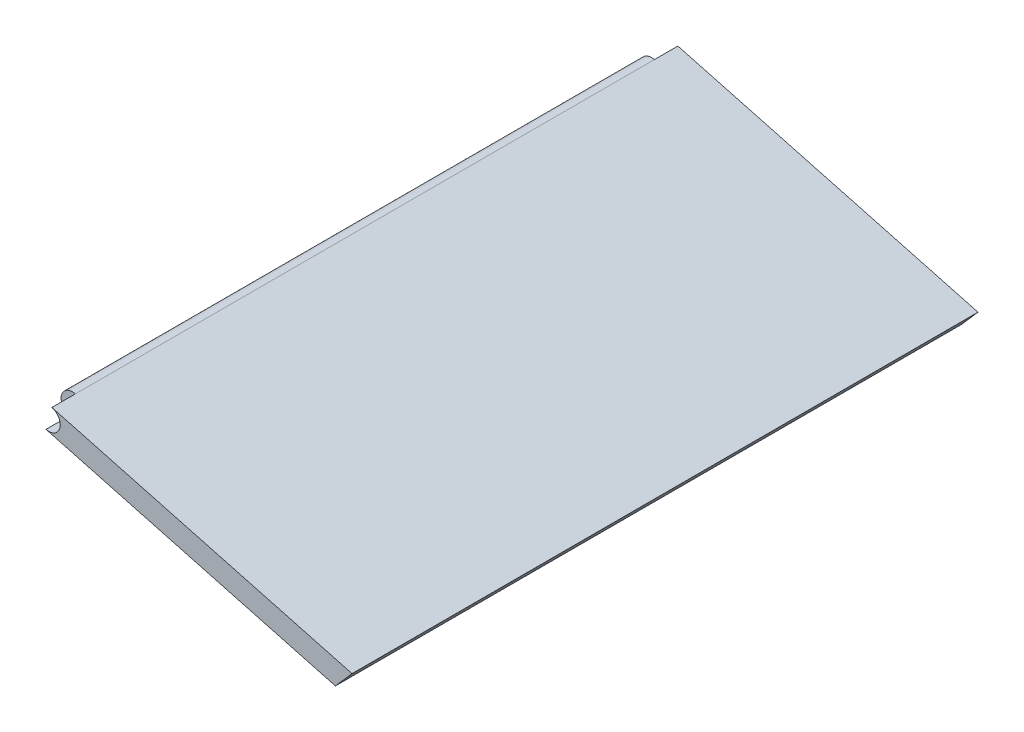
SolidWorks part; units mm, degrees
material "Reinblei"
ref_plane "Ebene vorne" through (0, 0, 0) normal (0, 0, 1) x (1, 0, 0)
ref_plane "Ebene oben" through (0, 0, 0) normal (0, 1, 0) x (1, 0, 0)
ref_plane "Ebene rechts" through (0, 0, 0) normal (1, 0, 0) x (0, 0, -1)
sketch "Skizze1" plane through (0, 0, 0) normal (0, 0, 1) x (1, 0, 0)
  line L0 (0, 0) -> (383.5885, -102.7822)
  line L1 (383.5885, -102.7822) -> (362.3381, -127.0882)
  line L2 (362.3381, -127.0882) -> (0, -30)
  line L3 (0, -30) -> (0, 0) construction
  line L4 (0, 0) -> (16.9676, 0) construction
  line L5 (0, 0) -> (-7.5, -27.9904)
  line L6 (-7.5, -27.9904) -> (0, -30)
  dimension "D1" = 15
  dimension "D2" = 30
  dimension "D3" = 397.12
  dimension "D4" = 375.12
extrude "Aufsatz-Linear austragen1" add sketch "Skizze1" along normal blind 800
sketch "Skizze3" plane through (0, 0, 0) normal (0, 0, -1) x (-1, 0, 0)
  line L1 (0, 0) -> (7.5, -27.9904) construction
  circle A1 centre (3.75, -13.9952) radius 14.4889
extrude "Aufsatz-Linear austragen2" add sketch "Skizze3" against normal up to surface (800 mm away) up to face at (184.6066, -64.4652, 800)
sketch "Skizze5" plane through (0, 0, 0) normal (0, 0, -1) x (-1, 0, 0)
  line L0 (0, 0) -> (7.5, -27.9904) construction
  circle A0 centre (3.75, -13.9952) radius 14.4889
extrude "Schnitt-Linear austragen1" cut sketch "Skizze5" against normal blind 30
pattern_linear "Lineares Muster1" count 2 spacing 770 along (0, 0, 1) of "Schnitt-Linear austragen1"
